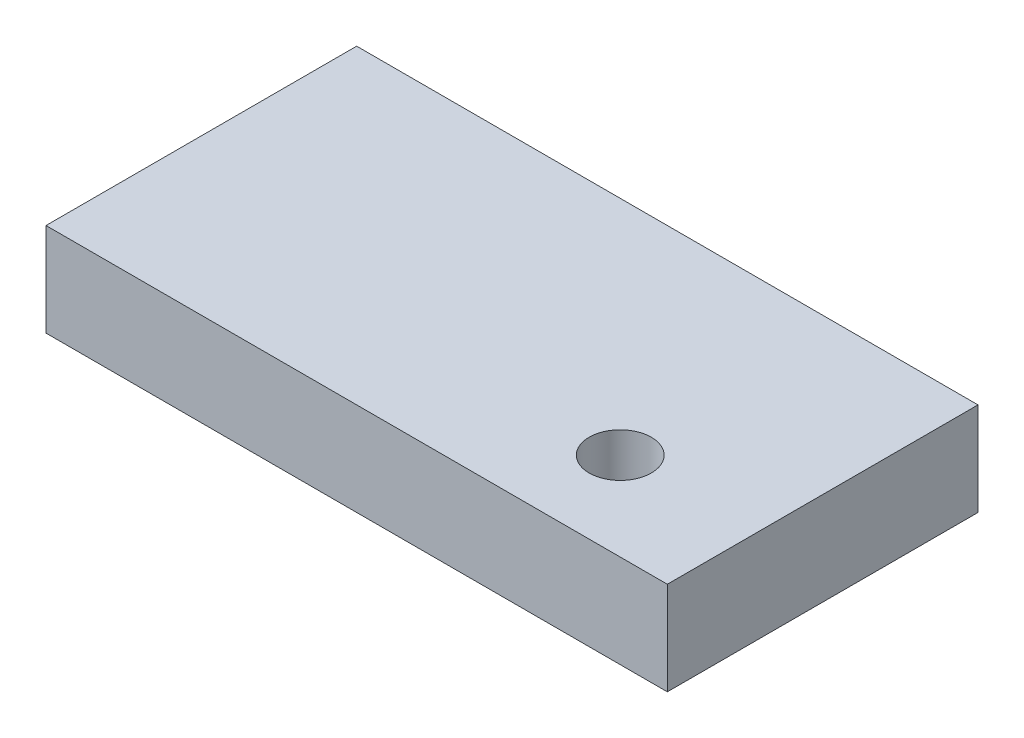
SolidWorks part; units mm, degrees
ref_plane "Front Plane" through (0, 0, 0) normal (0, 0, 1) x (1, 0, 0)
ref_plane "Top Plane" through (0, 0, 0) normal (0, 1, 0) x (1, 0, 0)
ref_plane "Right Plane" through (0, 0, 0) normal (1, 0, 0) x (0, 0, -1)
sketch "Sketch4" plane through (0, 0, 0) normal (0, 1, 0) x (1, 0, 0)
  line L1 (-50, -25) -> (50, -25)
  line L2 (-50, -25) -> (-50, 25)
  line L3 (-50, 25) -> (50, 25)
  line L4 (50, -25) -> (50, 25)
  line L5 (-50, -25) -> (50, 25) construction
  line L6 (-50, 25) -> (50, -25) construction
  point P0 (0, 0)
  dimension "D1" = 100
  dimension "D2" = 50
extrude "Boss-Extrude3" add sketch "Sketch4" along normal blind 15
sketch "Sketch5" plane through (0, 15, 0) normal (0, 1, 0) x (1, 0, 0)
  circle A0 centre (28.2098, -10.7939) radius 5
  dimension "D1" = 10
extrude "Cut-Extrude2" cut sketch "Sketch5" against normal blind 15
sketch "Sketch6" plane through (0, 15, 0) normal (0, 1, 0) x (1, 0, 0)
  point P0 (-27.8522, -15.482)
  point P1 (-28.6829, 0)
  point P2 (20.9054, 9.3333)
  point P3 (-13.0666, 15.576)
  point P4 (-5.2618, -13.8731)
  point P5 (-43.4452, 18.4742)
